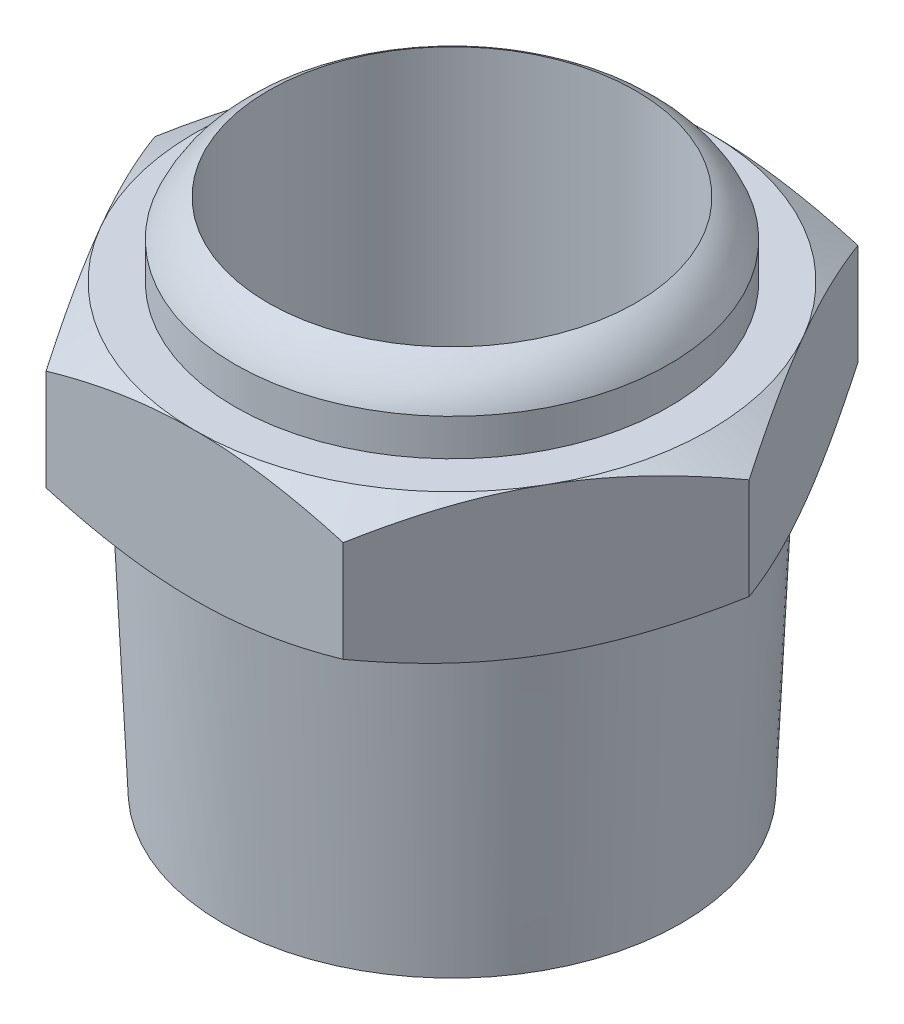
SolidWorks part; units mm, degrees
material "Brass"
ref_plane "Front Plane" through (0, 0, 0) normal (0, 0, 1) x (1, 0, 0)
ref_plane "Top Plane" through (0, 0, 0) normal (0, 1, 0) x (1, 0, 0)
ref_plane "Right Plane" through (0, 0, 0) normal (1, 0, 0) x (0, 0, -1)
sketch "HexBaseS" plane through (0, 0, 0) normal (0, 1, 0) x (1, 0, 0)
  line L0 (0, 0) -> (0, 7) construction
  line L1 (8.0829, 0) -> (4.0415, 7)
  line L2 (4.0415, 7) -> (-4.0415, 7)
  line L3 (-4.0415, 7) -> (-8.0829, 0)
  line L4 (-8.0829, 0) -> (-4.0415, -7)
  line L5 (-4.0415, -7) -> (4.0415, -7)
  line L6 (4.0415, -7) -> (8.0829, 0)
  circle A0 centre (0, 0) radius 7 construction
  dimension "Width" = 14
extrude "HexBase" add sketch "HexBaseS" along normal mid plane 4
sketch "TubeClampingHeadS" plane through (0, 2, 0) normal (0, 1, 0) x (1, 0, 0)
  line L1 (0, -7) -> (0, -5.9) construction
  line L2 (-4.0415, -7) -> (4.0415, -7) construction
  circle A0 centre (0, 0) radius 5.9
  dimension "RefDia" = 11.8
  dimension "DiaControl" = 1.1
extrude "TubeClampingHead" add sketch "TubeClampingHeadS" along normal blind 2
sketch "FasteningHeadS" plane through (0, -2, 0) normal (0, -1, 0) x (-1, 0, 0)
  circle A0 centre (0, 0) radius 6.5785
  dimension "MajorOD" = 13.157
extrude "FasteningHead" add sketch "FasteningHeadS" along normal blind 8 draft 2.5
cosmetic thread "Cosmetic Thread1" parameters "D2"=4.891
sketch "BoreFasteningHeadS" plane through (0, -10, 0) normal (0, -1, 0) x (1, 0, 0)
  circle A0 centre (0, 0) radius 4.7
  circle A1 centre (0, 0) radius 6.5785 construction
  dimension "DiaControl" = 1.8785
extrude "BoreFasteningHead" cut sketch "BoreFasteningHeadS" against normal blind 3.2
sketch "HexKeyS" plane through (0, -6.8, 0) normal (0, -1, 0) x (-1, 0, 0)
  line L1 (-1.4434, 2.5) -> (-2.8868, 0)
  line L2 (-2.8868, 0) -> (-1.4434, -2.5)
  line L3 (-1.4434, -2.5) -> (1.4434, -2.5)
  line L4 (1.4434, -2.5) -> (2.8868, 0)
  line L5 (2.8868, 0) -> (1.4434, 2.5)
  line L6 (1.4434, 2.5) -> (-1.4434, 2.5)
  circle A0 centre (0, 0) radius 2.5 construction
  dimension "D1" = 5
extrude "HexKey" cut sketch "HexKeyS" against normal through all
sketch "BoreTubeAccessS" plane through (0, 4, 0) normal (0, 1, 0) x (1, 0, 0)
  circle A0 centre (0, 0) radius 5
  circle A1 centre (0, 0) radius 5.9 construction
  dimension "D2" = 10
  dimension "RefDia" = 10
  dimension "DiaControl" = 0.9
extrude "BoreTubeAccess" cut sketch "BoreTubeAccessS" against normal offset from surface (9.8 mm away) 1 up to face at (0, -6.8, 0)
sketch "ClampingFeatureS" plane through (0, 0, 0) normal (0, 0, 1) x (1, 0, 0)
  line L0 (5, 4) -> (5.9, 4)
  line L1 (5.9, 4) -> (-5.9, 4) construction
  line L2 (5.9, 4) -> (5.9, 3)
  line L3 (5.9, 2) -> (5.9, 4) construction
  arc A1 (5.9, 3) -> (5, 4) centre (4.05, 2.24) ccw
  dimension "Radius" = 2
  dimension "Height" = 1
revolve "ClampingFeature" cut sketch "ClampingFeatureS" angle 360 about axis through (0, 4, 0) along (0, -1, 0)
sketch "ORingSeatS" plane through (0, -5.8, 0) normal (0, 1, 0) x (1, 0, 0)
  circle A0 centre (0, 0) radius 4
  circle A1 centre (0, 0) radius 5 construction
  circle A2 centre (0, 0) radius 5
  dimension "D2" = 8
  dimension "RefDia" = 8
  dimension "DiaControl" = 1
extrude "ORingSeat" add sketch "ORingSeatS" along normal blind 1.5
sketch "ChamferHexBaseS" plane through (0, 2, 0) normal (0, 1, 0) x (1, 0, 0)
  line L0 (8.0829, 0) -> (4.0415, 7) construction
  circle A0 centre (0, 0) radius 7
extrude "ChamferHexBase" cut sketch "ChamferHexBaseS" against normal through all draft 60 flip side to cut
mirror "CHB VM" about plane through (0, 0, 0) normal (0, 1, 0) of "ChamferHexBase"
